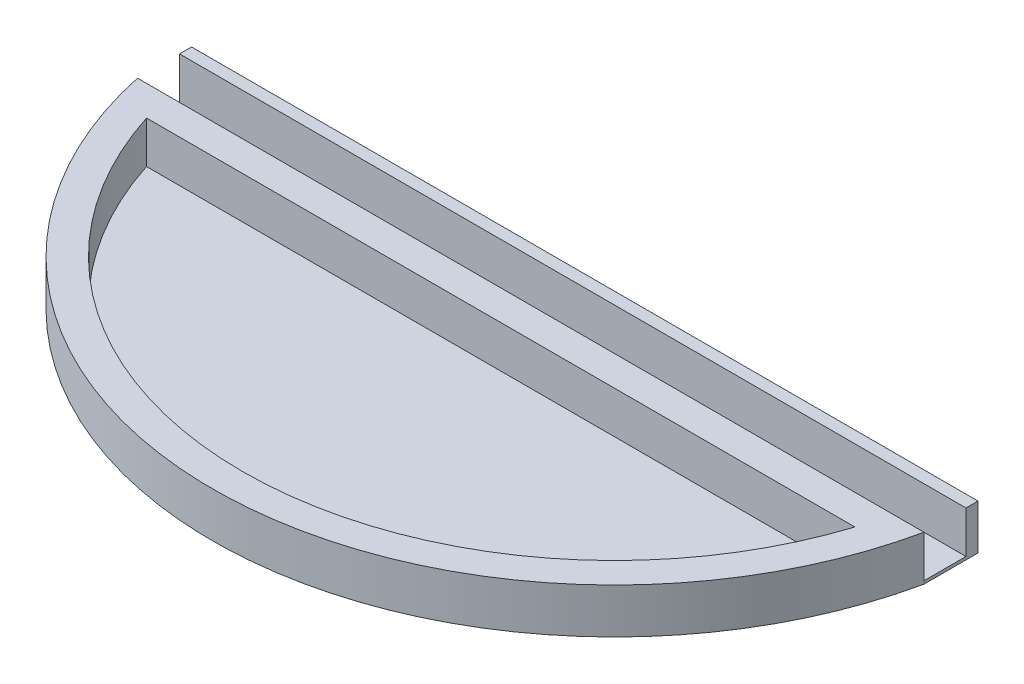
SolidWorks part; units mm, degrees
ref_plane "Front Plane" through (0, 0, 0) normal (0, 0, 1) x (1, 0, 0)
ref_plane "Top Plane" through (0, 0, 0) normal (0, 1, 0) x (1, 0, 0)
ref_plane "Right Plane" through (0, 0, 0) normal (1, 0, 0) x (0, 0, -1)
sketch "Sketch1" plane through (0, 0, 0) normal (0, 1, 0) x (1, 0, 0)
  line L2 (-64.5, 3.5) -> (64.5, 3.5)
  line L3 (-64.5, 3.5) -> (-64.5, -3.5)
  line L4 (-64.5, -3.5) -> (64.5, -3.5)
  line L5 (64.5, 3.5) -> (64.5, -3.5)
  line L6 (-64.5, 3.5) -> (64.5, -3.5) construction
  line L7 (-64.5, -3.5) -> (64.5, 3.5) construction
  line L8 (-65.5, 5.5) -> (-65.5, -3.5)
  line L11 (0, -3.5) -> (0, -70) construction
  line L12 (-65.5, 5.5) -> (65.5, 5.5)
  line L13 (65.5, 5.5) -> (65.5, -3.5)
  arc A1 (-65.5, -3.5) -> (65.5, -3.5) centre (0, 10.4741) ccw
  point P0 (0, 0)
  point P6 (0, 0)
  point P10 (0, -70)
  point P14 (0, -56.5)
  dimension "D2" = 7
  dimension "D4" = 53
  dimension "D1" = 129
  dimension "D3" = 131
  dimension "D5" = 2
extrude "Boss-Extrude1" add sketch "Sketch1" along normal blind 7
sketch "Sketch2" plane through (0, 0, 0) normal (0, -1, 0) x (1, 0, 0)
  line L3 (-65.5, -5.5) -> (65.5, -5.5)
  line L4 (65.5, -5.5) -> (65.5, 3.5)
  line L5 (-65.5, 3.5) -> (-65.5, -5.5)
  line L6 (-65.5, -5.5) -> (65.5, -5.5)
  line L7 (65.5, -5.5) -> (65.5, 3.5)
  line L8 (-65.5, 3.5) -> (-65.5, -5.5)
  arc A1 (65.5, 3.5) -> (-65.5, 3.5) centre (0, -10.4741) ccw
  arc A2 (65.5, 3.5) -> (-65.5, 3.5) centre (0, -10.4741) ccw
  dimension "D1" = 0
extrude "Boss-Extrude2" add sketch "Sketch2" along normal blind 0.5
sketch "Sketch3" plane through (0, 7, 0) normal (0, 1, 0) x (1, 0, 0)
  line L0 (-65.5, 5.5) -> (-65.5, -3.5) construction
  line L1 (-65.5, 3.5) -> (65.5, 3.5)
  line L2 (-65.5, 3.5) -> (-65.5, -3.5)
  line L3 (-65.5, -3.5) -> (65.5, -3.5)
  line L4 (65.5, 3.5) -> (65.5, -3.5)
  line L5 (65.5, -3.5) -> (65.5, 5.5) construction
  line L6 (64.5, 3.5) -> (-64.5, 3.5) construction
  line L7 (-64.5, -3.5) -> (64.5, -3.5) construction
extrude "Cut-Extrude4" cut sketch "Sketch3" against normal blind 7
sketch "Sketch4" plane through (0, 7, 0) normal (0, 1, 0) x (1, 0, 0)
  line L3 (58.998, -8.5) -> (-58.998, -8.5)
  line L4 (58.998, -8.5) -> (-58.998, -8.5)
  arc A3 (-58.998, -8.5) -> (58.998, -8.5) centre (0, 10.4741) ccw
  arc A4 (-58.998, -8.5) -> (58.998, -8.5) centre (0, 10.4741) ccw
  dimension "D1" = 5
extrude "Cut-Extrude5" cut sketch "Sketch4" against normal blind 7
